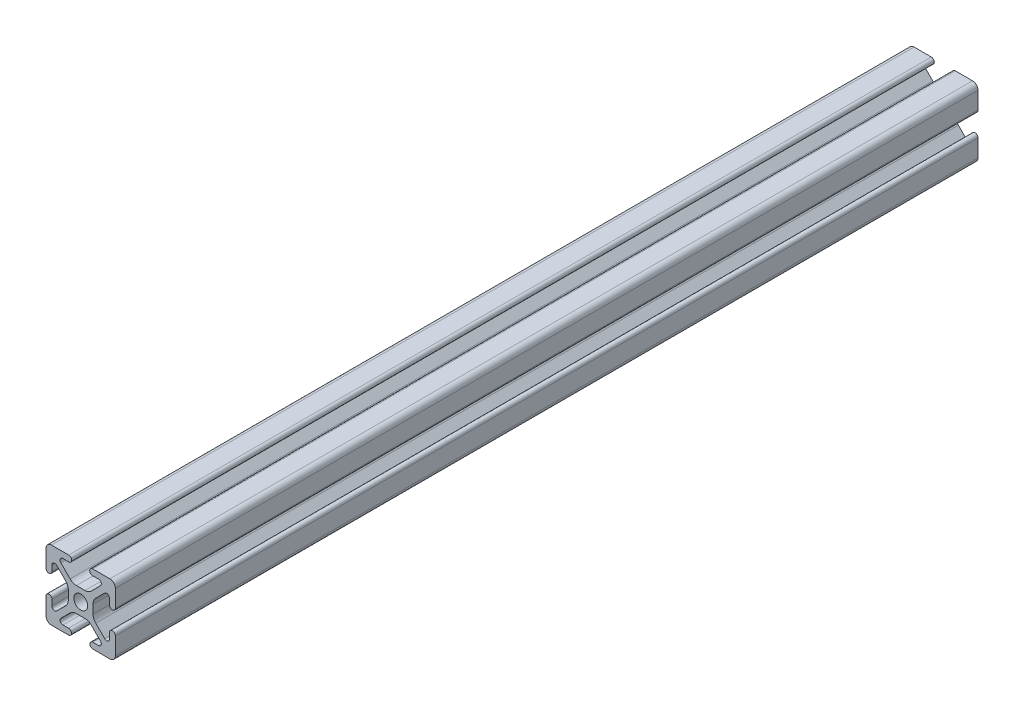
SolidWorks part; units mm, degrees
material "6005A-T61"
ref_plane "Front Plane" through (0, 0, 0) normal (0, 0, 1) x (1, 0, 0)
ref_plane "Top Plane" through (0, 0, 0) normal (0, 1, 0) x (1, 0, 0)
ref_plane "Right Plane" through (0, 0, 0) normal (1, 0, 0) x (0, 0, -1)
sketch "Sketch1" plane through (0, 0, 0) normal (0, 0, 1) x (1, 0, 0)
  line L0 (-8.6363, 7.1116) -> (-5.4322, 3.9121)
  line L1 (-4.455, 1.5554) -> (-4.455, -1.5554)
  line L2 (-5.4322, -3.9121) -> (-8.6363, -7.1116)
  line L3 (-10.36, -6.3969) -> (-10.36, -4.32)
  line L4 (-12.5, -4.32) -> (-12.5, -8.6518)
  line L5 (-12.5, -8.6518) -> (-12.5, -10.5371)
  line L6 (-10.5371, -12.5) -> (-8.4416, -12.5)
  line L7 (-8.4416, -12.5) -> (-4.3879, -12.5)
  line L8 (-4.3879, -10.36) -> (-6.42, -10.36)
  line L9 (-7.1337, -8.6353) -> (-3.7953, -5.3018)
  line L10 (-1.5554, -4.375) -> (1.5554, -4.375)
  line L11 (10.36, 4.32) -> (10.36, 6.3969)
  line L12 (12.5, 7.9913) -> (12.5, 4.32)
  line L13 (12.5, 10.5371) -> (12.5, 7.9913)
  line L14 (4.32, 12.5) -> (10.5371, 12.5)
  line L16 (6.42, 10.36) -> (4.32, 10.36)
  line L17 (3.7953, 5.3018) -> (7.1337, 8.6353)
  line L18 (7.1337, -8.6353) -> (3.7953, -5.3018)
  line L19 (4.3879, -10.36) -> (6.42, -10.36)
  line L20 (8.4416, -12.5) -> (4.3879, -12.5)
  line L21 (10.5371, -12.5) -> (8.4416, -12.5)
  line L22 (12.5, -8.6518) -> (12.5, -10.5371)
  line L23 (12.5, -4.32) -> (12.5, -8.6518)
  line L24 (10.36, -6.3969) -> (10.36, -4.32)
  line L25 (5.4322, -3.9121) -> (8.6363, -7.1116)
  line L26 (4.455, 1.5554) -> (4.455, -1.5554)
  line L27 (8.6363, 7.1116) -> (5.4322, 3.9121)
  line L28 (1.5554, 4.375) -> (-1.5554, 4.375)
  line L29 (-3.7953, 5.3018) -> (-7.1337, 8.6353)
  line L30 (-6.42, 10.36) -> (-4.32, 10.36)
  line L32 (-4.32, 12.5) -> (-10.5371, 12.5)
  line L33 (-12.5, 10.5371) -> (-12.5, 7.9913)
  line L34 (-12.5, 7.9913) -> (-12.5, 4.32)
  line L35 (-10.36, 4.32) -> (-10.36, 6.3969)
  line L36 (-15.7693, 0) -> (12.5, 0) construction
  line L37 (0, 13.9334) -> (0, -12.3541) construction
  circle A0 centre (0, 0) radius 2.5
  arc A1 (-8.6363, 7.1116) -> (-10.36, 6.3969) centre (-9.35, 6.3969) ccw
  arc A2 (-4.455, 1.5554) -> (-5.4322, 3.9121) centre (-7.7855, 1.5554) ccw
  arc A3 (-5.4322, -3.9121) -> (-4.455, -1.5554) centre (-7.7855, -1.5554) ccw
  arc A4 (-10.36, -6.3969) -> (-8.6363, -7.1116) centre (-9.35, -6.3969) ccw
  arc A5 (-10.36, -4.32) -> (-12.5, -4.32) centre (-11.43, -4.32) ccw
  arc A6 (-12.5, -10.5371) -> (-10.5371, -12.5) centre (-10.5371, -10.5371) ccw
  arc A7 (-4.3879, -12.5) -> (-4.3879, -10.36) centre (-4.3879, -11.43) ccw
  arc A8 (-7.1337, -8.6353) -> (-6.42, -10.36) centre (-6.42, -9.35) ccw
  arc A9 (-1.5554, -4.375) -> (-3.7953, -5.3018) centre (-1.5554, -7.545) ccw
  arc A10 (12.5, 4.32) -> (10.36, 4.32) centre (11.43, 4.32) cw
  arc A11 (10.5371, 12.5) -> (12.5, 10.5371) centre (10.5371, 10.5371) cw
  arc A12 (4.32, 10.36) -> (4.32, 12.5) centre (4.32, 11.43) cw
  arc A13 (6.42, 10.36) -> (7.1337, 8.6353) centre (6.42, 9.35) cw
  arc A14 (3.7953, 5.3018) -> (1.5554, 4.375) centre (1.5554, 7.545) cw
  arc A15 (1.5554, -4.375) -> (3.7953, -5.3018) centre (1.5554, -7.545) cw
  arc A16 (7.1337, -8.6353) -> (6.42, -10.36) centre (6.42, -9.35) cw
  arc A17 (4.3879, -12.5) -> (4.3879, -10.36) centre (4.3879, -11.43) cw
  arc A18 (12.5, -10.5371) -> (10.5371, -12.5) centre (10.5371, -10.5371) cw
  arc A19 (10.36, -4.32) -> (12.5, -4.32) centre (11.43, -4.32) cw
  arc A20 (10.36, -6.3969) -> (8.6363, -7.1116) centre (9.35, -6.3969) cw
  arc A21 (5.4322, -3.9121) -> (4.455, -1.5554) centre (7.7855, -1.5554) cw
  arc A22 (4.455, 1.5554) -> (5.4322, 3.9121) centre (7.7855, 1.5554) cw
  arc A23 (8.6363, 7.1116) -> (10.36, 6.3969) centre (9.35, 6.3969) cw
  arc A24 (-3.7953, 5.3018) -> (-1.5554, 4.375) centre (-1.5554, 7.545) ccw
  arc A25 (-6.42, 10.36) -> (-7.1337, 8.6353) centre (-6.42, 9.35) ccw
  arc A26 (-4.32, 10.36) -> (-4.32, 12.5) centre (-4.32, 11.43) ccw
  arc A27 (-10.5371, 12.5) -> (-12.5, 10.5371) centre (-10.5371, 10.5371) ccw
  arc A28 (-12.5, 4.32) -> (-10.36, 4.32) centre (-11.43, 4.32) ccw
  dimension "D4" = 14.86
  dimension "D5" = 2.14
  dimension "D6" = 6.5
  dimension "D7" = 8.75
  dimension "D8" = 1.01
  dimension "D9" = 3.17
  dimension "D14" = 5
  dimension "D1" = 25
  dimension "D2" = 8.91
  dimension "D3" = 12.5
  dimension "D12" = 2.14
extrude "Extrude1" add sketch "Sketch1" against normal blind 310.7516
equation "\"WallThickness\"= 0.5cm"
equation "\"BottomPlateX\"= 3ft"
equation "\"BottomPlateZ\"= 2ft"
equation "\"BottomPlateHoleD\"=((\"ArmPlateX\")^2+(\"ArmPlateDepth\")^2)^.5+ 10mm"
equation "\"ActuatorPinD\"= 6.35mm"
equation "\"ActuatorPinL\"= 15cm"
equation "\"Box-X\"= 40cm"
equation "\"Box-Z\"= 20cm"
equation "\"Box-Y\"= 30cm"
equation "\"ArmPlateThickness\"= .125in"
equation "\"ArmPlateX\"= 18in"
equation "\"ArmPlateDepth\"= 7.1875in"
equation "\"DCMotor1D\"= 65mm"
equation "\"DCMotor1L\"= 215mm"
equation "\"DCMotor1ShaftL\"= 30mm"
equation "\"DCMotor2X\"= 68mm"
equation "\"DCMotor2D\"= 65mm"
equation "\"DCMotor2L\"= 208mm"
equation "\"DCMotor2ShaftL\"= 39mm"
equation "\"DCMotor2ShaftD\"= 15mm"
equation "\"BenchDepth\"= 5cm"
equation "\"BenchH\"= 10cm"
equation "\"BenchL\"= 15cm"
equation "\"PillowBlockW\"= 5cm"
equation "\"PillowBlockCenterH\"= \"DCMotor2X\"/2"
equation "\"EncoderRadius\"= 19mm"
equation "\"EncoderShaftL\"= 15mm"
equation "\"EncoderL\"= 33mm"
equation "\"EncoderHousingThickness\"= 7.5mm"
equation "\"TurntableID\"= 70mm"
equation "\"TurntableInner2*t\" = (\"TurntableOD\"-\"TurntableID\")*.25 - 1mm"
equation "\"TurntableInnerHoleRadius\"= \"TurntableID\"*.5 + \"TurntableInner2*t\"*.5"
equation "\"TurntableOD\"= 120mm"
equation "\"TurntableOuterHoleRadius\" = \"TurntableOD\"*.5 - ((\"TurntableOD\"-\"TurntableID\")*.25-.5mm)*.5"
equation "\"2525Height\" = 30cm"
equation "\"LENGTH@Extrude1\"=\"2525Height\"-45mm+2.4016mm + 53.35mm"
